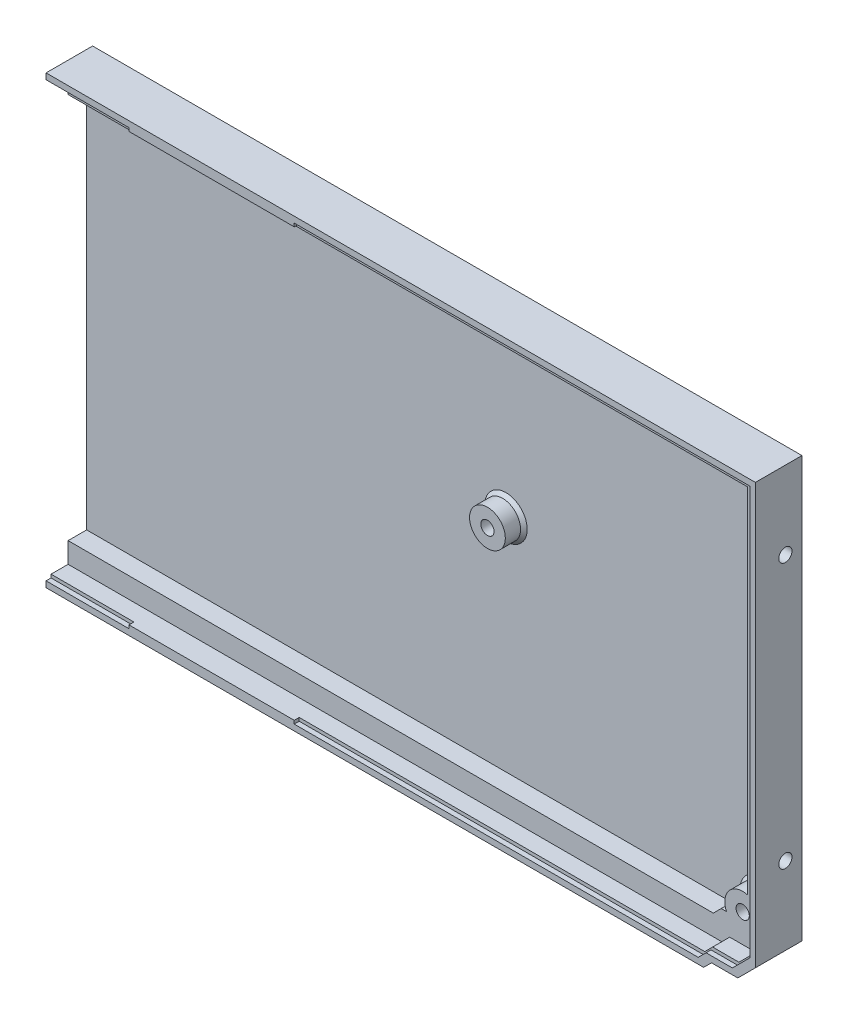
SolidWorks part; units mm, degrees
ref_plane "Přední rovina" through (0, 0, 0) normal (0, 0, 1) x (1, 0, 0)
ref_plane "Horní rovina" through (0, 0, 0) normal (0, 1, 0) x (1, 0, 0)
ref_plane "Pravá rovina" through (0, 0, 0) normal (1, 0, 0) x (0, 0, -1)
sketch "Skica3" plane through (0, 0, 0) normal (0, 0, 1) x (1, 0, 0)
  line L0 (0, 0) -> (415.1053, 0) construction
  line L1 (415.1053, 0) -> (416.6927, -1.5875) construction
  line L2 (416.6927, -1.5875) -> (416.6927, -119.8485) construction
  line L3 (0, 0) -> (-1.5875, -1.5875) construction
  line L4 (-1.5875, -1.5875) -> (-1.5875, -119.8485) construction
  line L5 (-1.5875, -119.8485) -> (0.7934, -122.2292) construction
  line L6 (0.7934, -122.2292) -> (8.7304, -122.2292) construction
  line L7 (8.7304, -122.2292) -> (11.1113, -124.61) construction
  line L8 (11.1113, -124.61) -> (403.9933, -124.61) construction
  line L9 (403.9933, -124.61) -> (406.3744, -122.2294) construction
  line L10 (406.3744, -122.2294) -> (414.3114, -122.2294) construction
  line L11 (416.6927, -119.8485) -> (414.3114, -122.2294) construction
  line L12 (2.4125, -4) -> (412.6927, -4)
  line L13 (412.6927, -4) -> (412.6927, -4)
  line L14 (412.6927, -4) -> (412.6927, -118.1914)
  line L15 (412.6927, -118.1914) -> (412.6547, -118.2294)
  line L16 (404.7177, -118.2294) -> (412.6547, -118.2294)
  line L17 (402.3367, -120.61) -> (404.7177, -118.2294)
  line L18 (12.7681, -120.61) -> (402.3367, -120.61)
  line L19 (10.3872, -118.2292) -> (12.7681, -120.61)
  line L20 (2.4502, -118.2292) -> (10.3872, -118.2292)
  line L21 (2.4125, -118.1915) -> (2.4502, -118.2292)
  line L22 (2.4125, -4) -> (2.4125, -118.1915)
  line L23 (2.4125, -4) -> (2.4125, -4)
  line L24 (-1.5875, -119.8485) -> (415.1053, 0) construction
  line L26 (0, 0) -> (416.6927, -119.8485) construction
  dimension "D1" = 135
  dimension "D2" = 135
  dimension "D3" = 4
  dimension "D4" = 2.245
  dimension "D5" = 2.245
  dimension "D6" = 118.261
  dimension "D7" = 118.261
  dimension "D8" = 3.367
  dimension "D9" = 7.937
  dimension "D10" = 3.367
  dimension "D11" = 392.882
  dimension "D12" = 3.367
  dimension "D13" = 7.937
  dimension "D14" = 3.3674
extrude "Přidat vysunutím1" add sketch "Skica3" along normal blind 5.6
shell "Skořepina1" thickness 1.8
sketch "Skica7" plane through (0, 0, 5.6) normal (0, 0, 1) x (1, 0, 0)
  line L20 (-6.5875, 5) -> (-6.5875, -121.9196)
  line L21 (-6.5875, -121.9196) -> (-1.2775, -127.2292)
  line L22 (-1.2775, -127.2292) -> (6.6595, -127.2292)
  line L23 (6.6595, -127.2292) -> (9.0403, -129.61)
  line L24 (9.0403, -129.61) -> (406.0641, -129.61)
  line L25 (406.0641, -129.61) -> (408.4452, -127.2294)
  line L26 (408.4452, -127.2294) -> (416.3822, -127.2294)
  line L27 (416.3822, -127.2294) -> (421.6927, -121.9198)
  line L28 (421.6927, -121.9198) -> (421.6927, 5)
  line L29 (421.6927, 5) -> (-6.5875, 5)
  line L30 (-6.5875, 5) -> (-6.5875, -121.9196)
  line L31 (-6.5875, -121.9196) -> (-1.2775, -127.2292)
  line L32 (-1.2775, -127.2292) -> (6.6595, -127.2292)
  line L33 (6.6595, -127.2292) -> (9.0403, -129.61)
  line L34 (9.0403, -129.61) -> (406.0641, -129.61)
  line L35 (406.0641, -129.61) -> (408.4452, -127.2294)
  line L36 (408.4452, -127.2294) -> (416.3822, -127.2294)
  line L37 (416.3822, -127.2294) -> (421.6927, -121.9198)
  line L38 (421.6927, -121.9198) -> (421.6927, 5)
  line L39 (421.6927, 5) -> (-6.5875, 5)
  line L40 (-3.7875, 2.2) -> (-3.7875, -120.7598)
  line L41 (-3.7875, -120.7598) -> (-0.1178, -124.4292)
  line L42 (-0.1178, -124.4292) -> (7.8192, -124.4292)
  line L43 (7.8192, -124.4292) -> (10.2001, -126.81)
  line L44 (10.2001, -126.81) -> (404.9045, -126.81)
  line L45 (404.9045, -126.81) -> (407.2855, -124.4294)
  line L46 (407.2855, -124.4294) -> (415.2225, -124.4294)
  line L47 (415.2225, -124.4294) -> (418.8927, -120.7598)
  line L48 (418.8927, -120.7598) -> (418.8927, 2.2)
  line L49 (418.8927, 2.2) -> (-3.7875, 2.2)
  line L50 (-3.7875, 2.2) -> (-3.7875, -120.7598)
  line L51 (-3.7875, -120.7598) -> (-0.1178, -124.4292)
  line L52 (-0.1178, -124.4292) -> (7.8192, -124.4292)
  line L53 (7.8192, -124.4292) -> (10.2001, -126.81)
  line L54 (10.2001, -126.81) -> (404.9045, -126.81)
  line L55 (404.9045, -126.81) -> (407.2855, -124.4294)
  line L56 (407.2855, -124.4294) -> (415.2225, -124.4294)
  line L57 (415.2225, -124.4294) -> (418.8927, -120.7598)
  line L58 (418.8927, -120.7598) -> (418.8927, 2.2)
  line L59 (418.8927, 2.2) -> (-3.7875, 2.2)
  dimension "D2" = 4.4
  dimension "D1" = 7.2
extrude "Přidat vysunutím3" add sketch "Skica7" along normal blind 5.15 separate body
sketch "Skica8" plane through (0, 0, 5.6) normal (0, 0, -1) x (-1, 0, 0)
  line L0 (-421.6927, 5) -> (6.5875, 5)
  line L1 (6.5875, 5) -> (6.5875, -121.9196)
  line L2 (6.5875, 5) -> (6.5875, -121.9196) construction
  line L3 (6.5875, -121.9196) -> (1.2775, -127.2292)
  line L4 (1.2775, -127.2292) -> (-6.6595, -127.2292)
  line L5 (-6.6595, -127.2292) -> (-9.0403, -129.61)
  line L6 (-9.0403, -129.61) -> (-406.0641, -129.61)
  line L7 (-406.0641, -129.61) -> (-408.4452, -127.2294)
  line L8 (-408.4452, -127.2294) -> (-416.3822, -127.2294)
  line L9 (-416.3822, -127.2294) -> (-421.6927, -121.9198)
  line L10 (-421.6927, -121.9198) -> (-421.6927, 5)
  line L11 (-0.6125, -2.2) -> (-0.6125, -118.9371)
  line L12 (-414.4927, -2.2) -> (-0.6125, -2.2) construction
  line L13 (-0.6125, -2.2) -> (-0.6125, -118.9371) construction
  line L14 (-0.6125, -118.9371) -> (-1.7047, -120.0292)
  line L15 (-1.7047, -120.0292) -> (-9.6417, -120.0292)
  line L16 (-9.6417, -120.0292) -> (-12.0226, -122.41)
  line L17 (-12.0226, -122.41) -> (-403.0822, -122.41)
  line L18 (-403.0822, -122.41) -> (-405.4632, -120.0294)
  line L19 (-405.4632, -120.0294) -> (-413.4002, -120.0294) construction
  line L20 (-405.4632, -120.0294) -> (-413.4002, -120.0294)
  line L21 (-413.4002, -120.0294) -> (-414.4927, -118.9371) construction
  line L22 (-413.4002, -120.0294) -> (-414.4927, -118.9371)
  line L23 (-414.4927, -118.9371) -> (-414.4927, -2.2)
  line L24 (-414.4927, -2.2) -> (-0.6125, -2.2)
extrude "Přidat vysunutím4" add sketch "Skica8" along normal up to surface (7.4 mm away) up to face at (207.5525, -96.7211, -1.8)
sketch "Skica11" plane through (0, 0, 10.75) normal (0, 0, 1) x (1, 0, 0)
  line L0 (207.5526, 3.195) -> (207.5526, 5) construction
  line L1 (421.6927, 5) -> (-6.5875, 5) construction
  line L2 (207.5522, -127.805) -> (207.5522, -129.61) construction
  line L3 (9.0403, -129.61) -> (406.0641, -129.61) construction
  line L4 (-4.9474, -58.4598) -> (-6.5875, -58.4598) construction
  line L5 (-6.5875, 5) -> (-6.5875, -121.9196) construction
  line L6 (420.0526, -58.4599) -> (421.6927, -58.4599) construction
  line L7 (421.6927, -121.9198) -> (421.6927, 5) construction
  line L8 (404.9045, -126.81) -> (407.2855, -124.4294) construction
  line L9 (415.2225, -124.4294) -> (418.8927, -120.7598) construction
  line L10 (7.8192, -124.4292) -> (10.2001, -126.81) construction
  line L11 (-3.7875, -120.7598) -> (-0.1178, -124.4292) construction
  line L13 (407.2855, -124.4294) -> (415.2225, -124.4294) construction
  line L14 (-0.1178, -124.4292) -> (7.8192, -124.4292) construction
  line L30 (420.0526, 3.195) -> (-4.9474, 3.195)
  line L31 (-4.9474, 3.195) -> (-4.9474, -120.1146)
  line L32 (-4.9474, -120.1146) -> (-0.24, -124.8217)
  line L33 (-0.24, -124.8217) -> (7.697, -124.8217)
  line L34 (7.697, -124.8217) -> (10.6804, -127.805)
  line L35 (10.6804, -127.805) -> (404.4241, -127.805)
  line L36 (404.4241, -127.805) -> (406.8051, -125.4244)
  line L37 (406.8051, -125.4244) -> (414.7421, -125.4244)
  line L38 (414.7421, -125.4244) -> (420.0526, -120.1148)
  line L39 (420.0526, -120.1148) -> (420.0526, 3.195)
  line L45 (421.6927, 5) -> (-6.5875, 5)
  line L46 (-6.5875, 5) -> (-6.5875, -121.9196)
  line L47 (-6.5875, -121.9196) -> (-1.2775, -127.2292)
  line L48 (-1.2775, -127.2292) -> (6.6595, -127.2292)
  line L49 (6.6595, -127.2292) -> (9.0403, -129.61)
  line L50 (9.0403, -129.61) -> (406.0641, -129.61)
  line L51 (406.0641, -129.61) -> (408.4452, -127.2294)
  line L52 (408.4452, -127.2294) -> (416.3822, -127.2294)
  line L53 (416.3822, -127.2294) -> (421.6927, -121.9198)
  line L54 (421.6927, -121.9198) -> (421.6927, 5)
  line L55 (421.6927, 5) -> (-6.5875, 5)
  line L56 (-6.5875, 5) -> (-6.5875, -121.9196)
  line L57 (-6.5875, -121.9196) -> (-1.2775, -127.2292)
  line L58 (-1.2775, -127.2292) -> (6.6595, -127.2292)
  line L59 (6.6595, -127.2292) -> (9.0403, -129.61)
  line L60 (9.0403, -129.61) -> (406.0641, -129.61)
  line L61 (406.0641, -129.61) -> (408.4452, -127.2294)
  line L62 (408.4452, -127.2294) -> (416.3822, -127.2294)
  line L63 (416.3822, -127.2294) -> (421.6927, -121.9198)
  line L64 (421.6927, -121.9198) -> (421.6927, 5)
  point P0 (207.5523, -63.11)
  point P2 (207.5523, -63.11)
  dimension "D1" = 131
  dimension "D2" = 425
  dimension "D3" = 0
extrude "Přidat vysunutím5" add sketch "Skica11" along normal blind 1.5
sketch "Skica14" plane through (0, 0, 10.75) normal (0, 0, 1) x (1, 0, 0)
  line L0 (418.8927, 2.2) -> (-3.7875, 2.2) construction
  line L1 (182.5326, 2.2) -> (132.6326, 2.2)
  line L2 (182.5326, 2.2) -> (182.5326, 3.195)
  line L3 (182.5326, 3.195) -> (132.6326, 3.195)
  line L4 (132.6326, 2.2) -> (132.6326, 3.195)
  line L5 (420.0526, 3.195) -> (-4.9474, 3.195) construction
  line L6 (418.8927, 2.2) -> (-3.7875, 2.2) construction
  line L7 (232.5726, 2.2) -> (282.4726, 2.2)
  line L8 (232.5726, 2.2) -> (232.5726, 3.195)
  line L9 (232.5726, 3.195) -> (282.4726, 3.195)
  line L10 (282.4726, 2.2) -> (282.4726, 3.195)
  line L11 (207.5526, 3.195) -> (207.5522, -127.805) construction
  line L12 (10.6804, -127.805) -> (404.4241, -127.805) construction
  line L13 (10.2001, -126.81) -> (404.9045, -126.81) construction
  line L14 (232.5722, -126.81) -> (282.4722, -126.81)
  line L15 (232.5722, -126.81) -> (232.5722, -127.805)
  line L16 (232.5722, -127.805) -> (282.4722, -127.805)
  line L17 (282.4722, -126.81) -> (282.4722, -127.805)
  line L18 (10.6804, -127.805) -> (404.4241, -127.805) construction
  line L20 (182.5322, -126.81) -> (132.6322, -126.81)
  line L21 (182.5322, -126.81) -> (182.5322, -127.805)
  line L22 (182.5322, -127.805) -> (132.6322, -127.805)
  line L23 (132.6322, -126.81) -> (132.6322, -127.805)
  dimension "D1" = 49.9
  dimension "D2" = 49.9
  dimension "D3" = 25.02
  dimension "D4" = 25.02
  dimension "D5" = 49.9
  dimension "D6" = 49.9
  dimension "D7" = 25.02
  dimension "D8" = 25.02
extrude "Přidat vysunutím6" add sketch "Skica14" along normal up to surface (1.5 mm away) up to face at (207.5524, -100.1977, 12.25)
sketch "Skica15" plane through (0, 0, 0) normal (0, 0, 1) x (1, 0, 0)
  line L1 (34.9015, 4.5) -> (37.9015, 4.5)
  line L2 (34.9015, 4.5) -> (34.9015, -4.5)
  line L3 (34.9015, -4.5) -> (37.9015, -4.5)
  line L4 (37.9015, 4.5) -> (37.9015, -4.5)
  line L5 (34.9015, 4.5) -> (37.9015, -4.5) construction
  line L6 (34.9015, -4.5) -> (37.9015, 4.5) construction
  line L20 (-1.5875, 0) -> (-1.5875, -119.8485)
  line L21 (-1.5875, -119.8485) -> (0.7934, -122.2292)
  line L22 (0.7934, -122.2292) -> (8.7304, -122.2292)
  line L23 (8.7304, -122.2292) -> (11.1113, -124.61)
  line L24 (11.1113, -124.61) -> (403.9933, -124.61)
  line L25 (403.9933, -124.61) -> (406.3744, -122.2294)
  line L26 (406.3744, -122.2294) -> (414.3114, -122.2294)
  line L27 (414.3114, -122.2294) -> (416.6927, -119.8485)
  line L28 (416.6927, -119.8485) -> (416.6927, 0)
  line L29 (416.6927, 0) -> (-1.5875, 0)
  line L30 (-1.5875, 0) -> (-1.5875, -119.8485) construction
  line L31 (-1.5875, -119.8485) -> (0.7934, -122.2292) construction
  line L32 (0.7934, -122.2292) -> (8.7304, -122.2292) construction
  line L33 (8.7304, -122.2292) -> (11.1113, -124.61) construction
  line L34 (11.1113, -124.61) -> (403.9933, -124.61) construction
  line L35 (403.9933, -124.61) -> (406.3744, -122.2294) construction
  line L36 (406.3744, -122.2294) -> (414.3114, -122.2294) construction
  line L37 (414.3114, -122.2294) -> (416.6927, -119.8485) construction
  line L38 (416.6927, -119.8485) -> (416.6927, 0) construction
  line L39 (416.6927, 0) -> (-1.5875, 0) construction
  circle A0 centre (3.9685, -115.9542) radius 5.4
  circle A1 centre (33.4915, -69.051) radius 5.4
  circle A2 centre (411.1977, -115.8794) radius 5.4
  circle A3 centre (334.1477, -53.972) radius 5.4
  point P2 (-1.4315, -115.9542)
  point P3 (3.9685, -121.3542)
  point P4 (28.0915, -69.051)
  point P8 (33.4915, -74.451)
  point P12 (411.1977, -121.2794)
  point P13 (416.5977, -115.8794)
  point P17 (334.1477, -48.572)
  point P19 (339.5477, -53.972)
  point P21 (36.4015, 0)
  point P23 (36.4015, 0)
  dimension "D2" = 0.156
  dimension "D4" = 10.8
  dimension "D7" = 10.8
  dimension "D10" = 10.8
  dimension "D13" = 10.8
  dimension "D3" = 0.875
  dimension "D5" = 29.679
  dimension "D6" = 50.159
  dimension "D8" = 0.095
  dimension "D9" = 0.95
  dimension "D11" = 77.145
  dimension "D12" = 48.572
  dimension "D14" = 37.989
  dimension "D15" = 9
  dimension "D16" = 3
  dimension "D1" = 4
extrude "Přidat vysunutím7" add sketch "Skica15" along normal blind 5.6
sketch "Skica16" plane through (0, 0, 5.6) normal (0, 0, 1) x (1, 0, 0)
  circle A0 centre (3.9685, -115.9542) radius 2
  circle A1 centre (33.4915, -69.051) radius 2
  circle A2 centre (334.1477, -53.972) radius 2
  circle A3 centre (411.1977, -115.8794) radius 2
  dimension "D1" = 4
  dimension "D2" = 4
  dimension "D3" = 4
  dimension "D4" = 4
extrude "Odebrat vysunutím1" cut sketch "Skica16" against normal blind 5.75
chamfer "Zkosení1" distance 1 angle 45 4 edges at (407.0694, -112.3984, 0) (8.0492, -112.4175, 0) (38.8915, -69.051, 0) (339.5477, -53.972, 0)
sketch "Skica17" plane through (0, 0, 5.6) normal (0, 0, 1) x (1, 0, 0)
  line L0 (34.9015, -4.5) -> (37.9015, -4.5) construction
  line L1 (24.4015, -11.2) -> (48.4015, -11.2)
  line L2 (24.4015, -11.2) -> (24.4015, 2.2)
  line L3 (24.4015, 2.2) -> (48.4015, 2.2)
  line L4 (48.4015, -11.2) -> (48.4015, 2.2)
  line L5 (24.4015, -11.2) -> (48.4015, 2.2) construction
  line L6 (24.4015, 2.2) -> (48.4015, -11.2) construction
  line L7 (418.8927, 2.2) -> (-3.7875, 2.2) construction
  point P0 (36.4015, -4.5)
  dimension "D1" = 24
extrude "Odebrat vysunutím2" cut sketch "Skica17" against normal blind 1.6
sketch "Skica18" plane through (0, -4.5, 0) normal (0, -1, 0) x (1, 0, 0)
  line L0 (33.6515, 4) -> (39.1515, 4) construction
  line L1 (37.9015, 4) -> (34.9015, 4) construction
  line L2 (37.9015, 4) -> (48.4015, 4) construction
  line L3 (33.6515, 7.5) -> (39.1515, 7.5)
  line L4 (33.6515, 0.5) -> (39.1515, 0.5)
  arc A0 (33.6515, 7.5) -> (33.6515, 0.5) centre (33.6515, 4) ccw
  arc A1 (39.1515, 0.5) -> (39.1515, 7.5) centre (39.1515, 4) ccw
  point P6 (36.4015, 4)
  point P11 (30.1515, 4)
  point P12 (42.6515, 4)
  dimension "D1" = 12.5
  dimension "D2" = 7
extrude "Odebrat vysunutím3" cut sketch "Skica18" against normal up to surface (9.5 mm away) up to face at (207.5526, 5, 5.225)
sketch "Skica23" plane through (-6.5875, 0, 0) normal (-1, 0, 0) x (0, 0, 1)
  line L2 (-1.8, 5) -> (-1.8, -121.9196) construction
  line L4 (-1.8, -58.4598) -> (12.25, -58.4598) construction
  line L5 (12.25, 5) -> (12.25, -121.9196) construction
  circle A0 centre (3.2, -18.4598) radius 2
  circle A1 centre (3.2, -98.4598) radius 2
  point P8 (-1.8, -58.4598)
  dimension "D2" = 4
  dimension "D3" = 4
  dimension "D1" = 40
  dimension "D4" = 5
extrude "Odebrat vysunutím4" cut sketch "Skica23" against normal blind 5.7
sketch "Skica24" plane through (421.6927, 0, 0) normal (1, 0, 0) x (0, 0, -1)
  line L0 (1.8, -58.4599) -> (-12.25, -58.4599) construction
  line L1 (1.8, -121.9198) -> (1.8, 5) construction
  line L2 (-12.25, -121.9198) -> (-12.25, 5) construction
  circle A0 centre (-3.2, -18.4599) radius 2
  circle A1 centre (-3.2, -98.4599) radius 2
  dimension "D1" = 4
  dimension "D2" = 4
  dimension "D3" = 40
  dimension "D4" = 5
extrude "Odebrat vysunutím5" cut sketch "Skica24" against normal blind 5.7
sketch "Skica25" plane through (0, 0, -1.8) normal (0, 0, -1) x (-1, 0, 0)
  line L0 (-421.6927, -121.9198) -> (-421.6927, 5) construction
  line L1 (-421.6927, 5) -> (6.5875, 5) construction
  line L2 (6.5875, 5) -> (6.5875, -121.9196) construction
  line L3 (-9.0403, -129.61) -> (-406.0641, -129.61) construction
  circle A0 centre (-401.6927, -15) radius 6.25
  circle A1 centre (-13.4125, -15) radius 6.25
  circle A2 centre (-388.4452, -109.61) radius 6.25
  circle A3 centre (-26.6595, -109.61) radius 6.25
  dimension "D1" = 12.5
  dimension "D2" = 12.5
  dimension "D3" = 12.5
  dimension "D4" = 12.5
  dimension "D5" = 20
  dimension "D6" = 20
  dimension "D7" = 20
  dimension "D8" = 20
  dimension "D9" = 20
  dimension "D10" = 20
  dimension "D11" = 20
  dimension "D12" = 20
extrude "Odebrat vysunutím6" cut sketch "Skica25" against normal blind 1.5
sketch "Skica26" plane through (0, 5, 0) normal (0, 1, 0) x (1, 0, 0)
  line L0 (421.6927, -12.25) -> (-6.5875, -12.25) construction
  line L1 (207.5526, -12.25) -> (-6.5875, -12.25)
  line L2 (207.5526, -12.25) -> (207.5526, 1.8)
  line L3 (207.5526, 1.8) -> (-6.5875, 1.8)
  line L4 (-6.5875, -12.25) -> (-6.5875, 1.8)
extrude "Odebrat vysunutím7" cut sketch "Skica26" against normal through all
